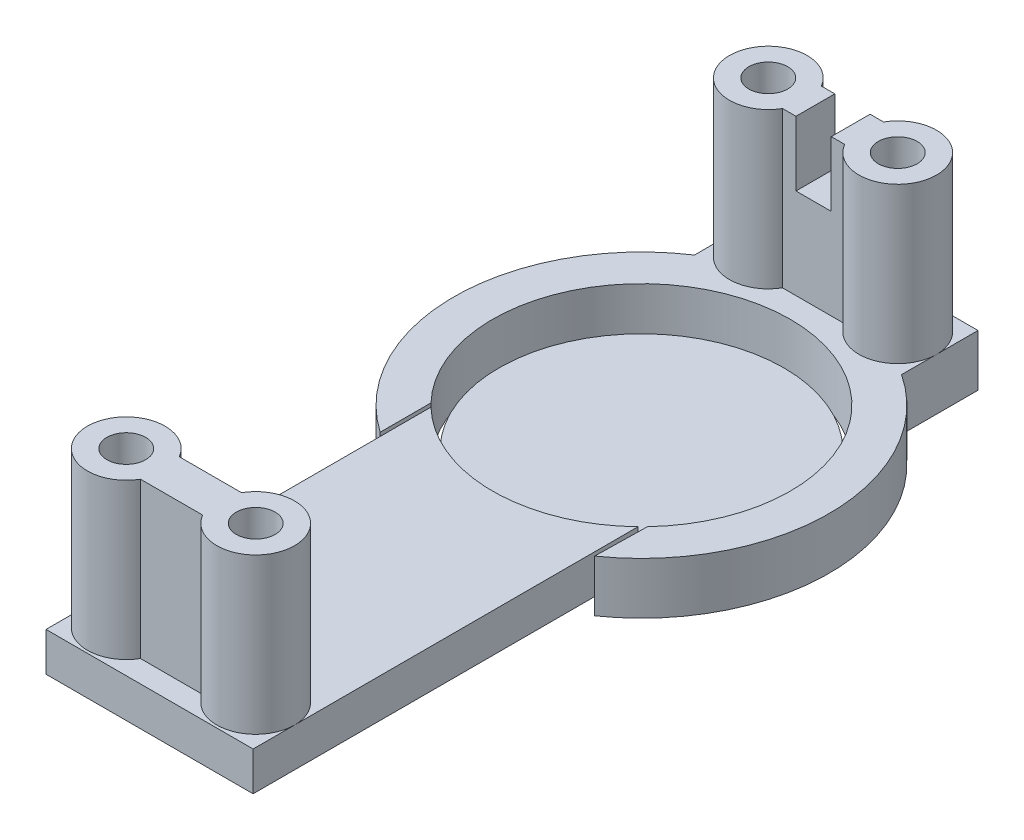
SolidWorks part; units mm, degrees
ref_plane "前视基准面" through (0, 0, 0) normal (0, 0, 1) x (1, 0, 0)
ref_plane "上视基准面" through (0, 0, 0) normal (0, 1, 0) x (1, 0, 0)
ref_plane "右视基准面" through (0, 0, 0) normal (1, 0, 0) x (0, 0, -1)
other "Configuration Table"
sketch "草图1" plane through (0, 0, 0) normal (0, 1, 0) x (1, 0, 0)
  line L1 (-5, 24.8) -> (5, 24.8) construction
  line L2 (-5, 24.8) -> (-5, -24.8) construction
  line L3 (-5, -24.8) -> (5, -24.8) construction
  line L4 (5, 24.8) -> (5, -24.8) construction
  line L5 (-5, 24.8) -> (5, -24.8) construction
  line L6 (-5, -24.8) -> (5, 24.8) construction
  line L7 (-8, 28) -> (8, 28)
  line L8 (-8, 28) -> (-8, -28)
  line L9 (-8, -28) -> (8, -28)
  line L10 (8, 28) -> (8, -28)
  line L11 (-8, 28) -> (8, -28) construction
  line L12 (-8, -28) -> (8, 28) construction
  circle A0 centre (-5, 24.8) radius 1.5
  circle A1 centre (5, 24.8) radius 1.5
  circle A2 centre (5, -24.8) radius 1.5
  circle A3 centre (-5, -24.8) radius 1.5
  point P0 (0, 0)
  point P10 (0, 0)
  dimension "D3" = 3
  dimension "D4" = 3
  dimension "D5" = 3
  dimension "D6" = 3
  dimension "D1" = 49.6
  dimension "D2" = 10
  dimension "D7" = 16
  dimension "D8" = 56
extrude "凸台-拉伸1" add sketch "草图1" along normal blind 3
sketch "草图2" plane through (0, 3, 0) normal (0, 1, 0) x (1, 0, 0)
  line L0 (-2.4019, 26.3) -> (2.4019, 26.3)
  line L1 (-2.4019, 23.3) -> (2.4019, 23.3)
  line L2 (-8, 0) -> (8, 0) construction
  line L3 (-8, 28) -> (-8, -28) construction
  line L4 (8, -28) -> (8, 28) construction
  line L5 (-2.4019, -23.3) -> (2.4019, -23.3)
  line L6 (-2.4019, -26.3) -> (2.4019, -26.3)
  circle A0 centre (-5, 24.8) radius 3
  circle A1 centre (-5, 24.8) radius 1.5
  circle A2 centre (5, 24.8) radius 1.5
  circle A3 centre (5, 24.8) radius 3
  circle A4 centre (-5, -24.8) radius 1.5
  circle A5 centre (-5, -24.8) radius 3
  circle A6 centre (5, -24.8) radius 1.5
  circle A7 centre (5, -24.8) radius 3
  circle M1 centre (5, -24.8) radius 1.5
  circle M2 centre (-5, 24.8) radius 1.5
  circle M7 centre (5, 24.8) radius 1.5
  circle M8 centre (-5, -24.8) radius 1.5
extrude "凸台-拉伸3" add sketch "草图2" along normal blind 12 contours A0 M2 | A3 L0 A0 L1 | A3 M7 | A5 M8 | A7 L5 A5 L6 | A7 M1
sketch "草图3" plane through (0, 3, 0) normal (0, 1, 0) x (1, 0, 0)
  line L0 (8, 18.2614) -> (8, 22.0934)
  line L1 (8, -24.8) -> (8, 24.8) construction
  line L2 (8.2857, -1.8995) -> (8.3636, 2.107)
  line L3 (-8.2857, -1.8995) -> (-8.2857, 2.0252)
  line L4 (-8, 18.2614) -> (-8, 22.0934)
  line L5 (-8, 24.8) -> (-8, -24.8) construction
  circle A0 centre (0, 10) radius 11.5 construction
  arc A1 (8.3636, 2.107) -> (8, 18.2614) centre (0, 10) ccw
  arc A2 (8.2857, -1.8995) -> (8, 22.0934) centre (0, 10) ccw
  circle A3 centre (0, 10) radius 14.5 construction
  circle A4 centre (0, 10) radius 11.5 construction
  arc A5 (-8, 18.2614) -> (-8.2857, 2.0252) centre (0, 10) ccw
  arc A6 (-8, 22.0934) -> (-8.2857, -1.8995) centre (0, 10) ccw
  dimension "D1" = 3
extrude "凸台-拉伸4" add sketch "草图3" against normal blind 3
sketch "草图5" plane through (0, 0, 0) normal (0, -1, 0) x (1, 0, 0)
  circle A0 centre (0, -10) radius 11.5
extrude "切除-拉伸1" cut sketch "草图5" against normal blind 3
sketch "草图6" plane through (0, 15, 0) normal (0, 1, 0) x (1, 0, 0)
  line L0 (-2.4019, -26.3) -> (2.4019, -26.3) construction
  line L1 (1.3626, -26.3) -> (-1.3626, -26.3)
  line L2 (0, -26.3) -> (0, 26.3) construction
  line L3 (1.3626, 26.3) -> (-1.3626, 26.3)
  line L4 (-1.3626, -26.3) -> (-1.3626, 26.3)
  line L5 (-2.4019, 26.3) -> (2.4019, 26.3) construction
  line L6 (1.3626, -26.3) -> (1.3626, 26.3)
extrude "切除-拉伸2" cut sketch "草图6" against normal blind 5
sketch "草图7" plane through (0, 0, 0) normal (0, -1, 0) x (1, 0, 0)
  line L5 (-8.2857, -2.0252) -> (-8.2857, 1.8995)
  line L6 (-8, -22.0934) -> (-8, -28)
  line L7 (-8, -28) -> (8, -28)
  line L8 (8, -28) -> (8, -22.0934)
  line L9 (-8.2857, -2.0252) -> (-8.2857, 1.8995)
  line L10 (8.2857, 1.8995) -> (8.3636, -2.107)
  line L11 (8.2857, 1.8995) -> (8.3636, -2.107)
  line L12 (-8, -22.0934) -> (-8, -28)
  line L13 (-8, -28) -> (8, -28)
  line L14 (8, -28) -> (8, -22.0934)
  circle A0 centre (-5, 24.8) radius 1.5
  circle A1 centre (5, 24.8) radius 1.5
  arc A2 (-8.2857, 1.8995) -> (-8, -22.0934) centre (0, -10) ccw
  arc A3 (8, -22.0934) -> (8.2857, 1.8995) centre (0, -10) ccw
  arc A4 (-8.2857, 1.8995) -> (-8, -22.0934) centre (0, -10) ccw
  arc A5 (8, -22.0934) -> (8.2857, 1.8995) centre (0, -10) ccw
  circle A6 centre (0, -10) radius 11
  circle A7 centre (-5, -24.8) radius 1.5
  circle A8 centre (5, -24.8) radius 1.5
  arc A12 (-8.2857, -2.0252) -> (8.3636, -2.107) centre (0, -10) ccw
  arc A13 (-8.2857, -2.0252) -> (8.3636, -2.107) centre (0, -10) ccw
  dimension "D1" = 0
extrude "凸台-拉伸5" add sketch "草图7" along normal blind 1
